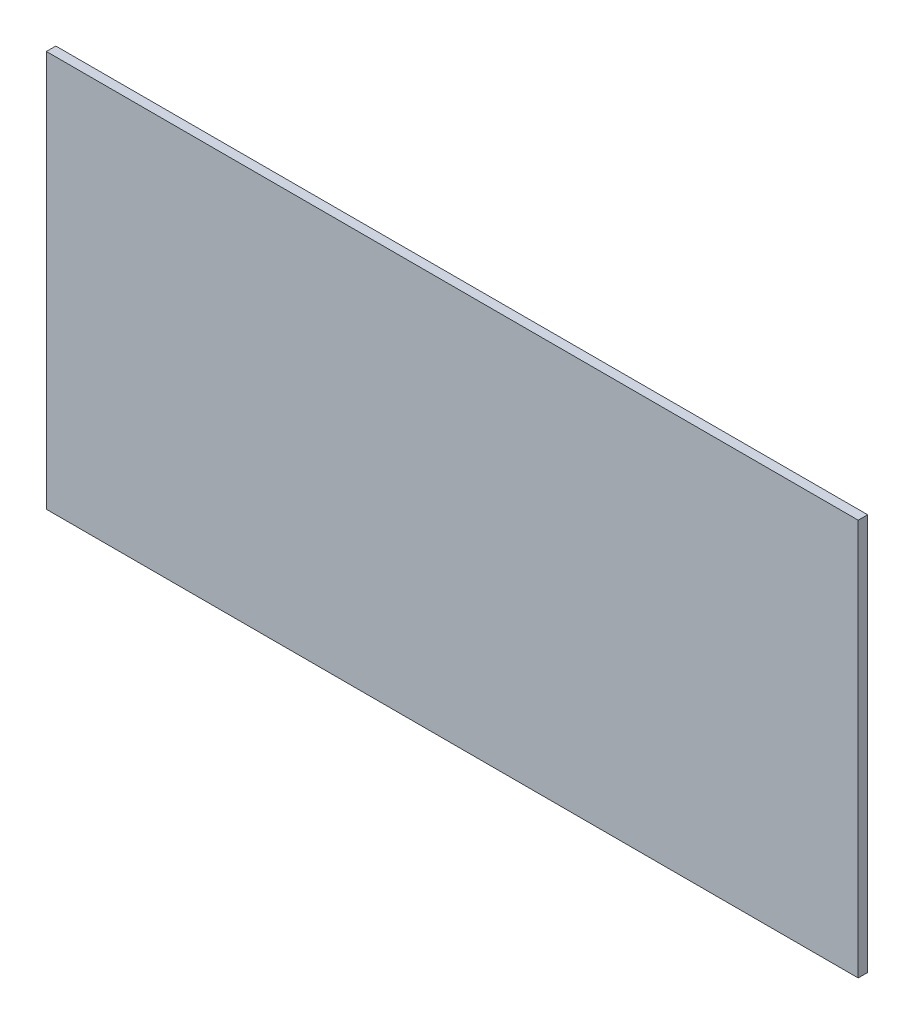
SolidWorks part; units mm, degrees
ref_plane "Front Plane" through (0, 0, 0) normal (0, 0, 1) x (1, 0, 0)
ref_plane "Top Plane" through (0, 0, 0) normal (0, 1, 0) x (1, 0, 0)
ref_plane "Right Plane" through (0, 0, 0) normal (1, 0, 0) x (0, 0, -1)
sketch "Sketch1" plane through (0, 0, 0) normal (0, 0, 1) x (1, 0, 0)
  line L1 (0, 0) -> (86, 0)
  line L2 (0, 0) -> (0, 42)
  line L3 (0, 42) -> (86, 42)
  line L4 (86, 0) -> (86, 42)
  dimension "D1" = 86
  dimension "D2" = 42
extrude "Profile" add sketch "Sketch1" along normal blind 1
equation "\"Profile_Depth\" = 1mm"
equation "\"D1@Profile\" = \"Profile_Depth\""
equation "\"EnvelopeWidth\" = 86mm"
equation "\"EnvelopeHeight\" = 42mm"
